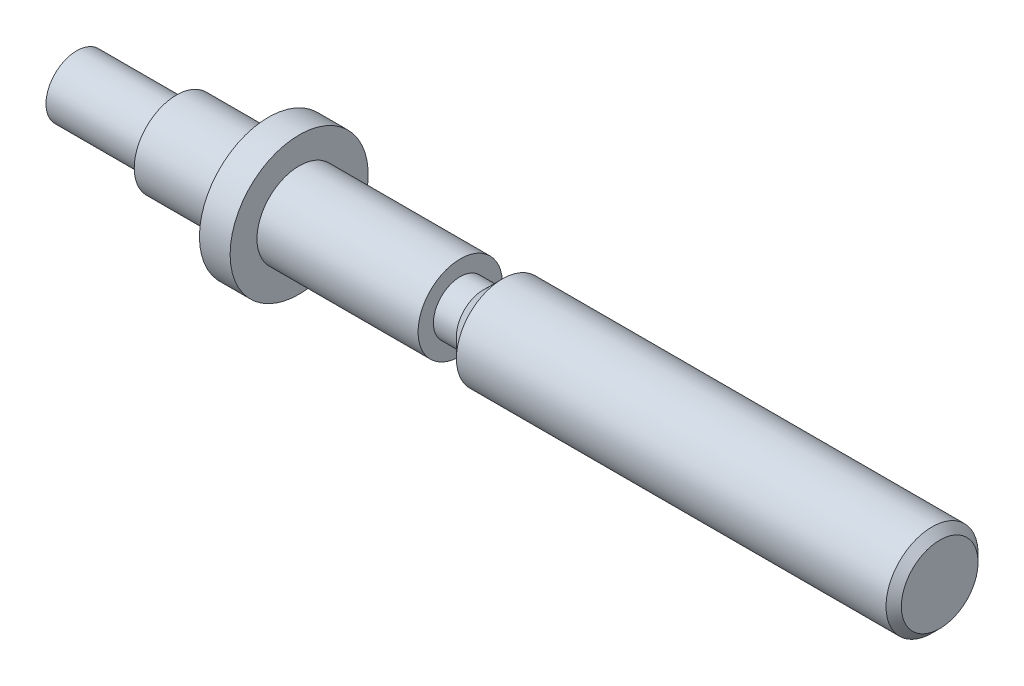
SolidWorks part; units mm, degrees
ref_plane "Plan de face" through (0, 0, 0) normal (0, 0, 1) x (1, 0, 0)
ref_plane "Plan de dessus" through (0, 0, 0) normal (0, 1, 0) x (1, 0, 0)
ref_plane "Plan de droite" through (0, 0, 0) normal (1, 0, 0) x (0, 0, -1)
sketch "Esquisse1" plane through (0, 0, 0) normal (0, 0, 1) x (1, 0, 0)
  line L0 (-83.6942, 0) -> (105.0576, 0) construction
  line L1 (0, 0) -> (0, 4)
  line L2 (0, 4) -> (13, 4)
  line L3 (13, 4) -> (13, 5.5)
  line L4 (13, 5.5) -> (25, 5.5)
  line L5 (25, 5.5) -> (25, 9)
  line L6 (25, 9) -> (29, 9)
  line L7 (29, 9) -> (29, 5.5)
  line L8 (29, 5.5) -> (50, 5.5)
  line L9 (50, 5.5) -> (50, 3.5)
  line L10 (50, 3.5) -> (53, 3.5)
  line L11 (53, 3.5) -> (55.5, 6)
  line L12 (55.5, 6) -> (111.5, 6)
  line L13 (111.5, 6) -> (112.5, 5)
  line L14 (112.5, 5) -> (112.5, 0)
  line L15 (112.5, 0) -> (0, 0)
  dimension "D1" = 5.5
  dimension "D2" = 4
  dimension "D3" = 13
  dimension "D4" = 9
  dimension "D5" = 4
  dimension "D6" = 12
  dimension "D7" = 5.5
  dimension "D8" = 21
  dimension "D9" = 3.5
  dimension "D10" = 3
  dimension "D11" = 6
  dimension "D12" = 45
  dimension "D13" = 1
  dimension "D14" = 57
revolve "Révolution1" add sketch "Esquisse1" angle 360 about L0
cosmetic thread "Représentation de filetage1" parameters "D1"=59.5, "D2"=10
hole_wizard "Trou taraudé M42" positions "Esquisse9" profile "Esquisse8" tap size "M4" standard "ISO"
sketch "Esquisse9" plane through (0, 0, 0) normal (-1, 0, 0) x (0, 0, 1)
  point P3 (0, 0)
sketch "Esquisse8" plane through (0, 0, 0) normal (0, 1, 0) x (0, 0, 1)
  line L0 (0, 0) -> (0, 12.0914)
  line L1 (0, 12.0914) -> (1.65, 11.1)
  line L2 (1.65, 11.1) -> (1.65, 0)
  line L5 (1.65, 0) -> (0, 0)
  line L10 (0, 12.0914) -> (-1.65, 11.1) construction
  line L11 (0, -6.35) -> (0, 107.95) construction
  dimension "Diamètre du trou pour taraudage" = 3.3
  dimension "Profondeur du trou pour taraudage" = 11.1
  dimension "Angle de pointe" = 118
cosmetic thread "Filetage de perçage3" parameters "D1"=9, "D2"=4
